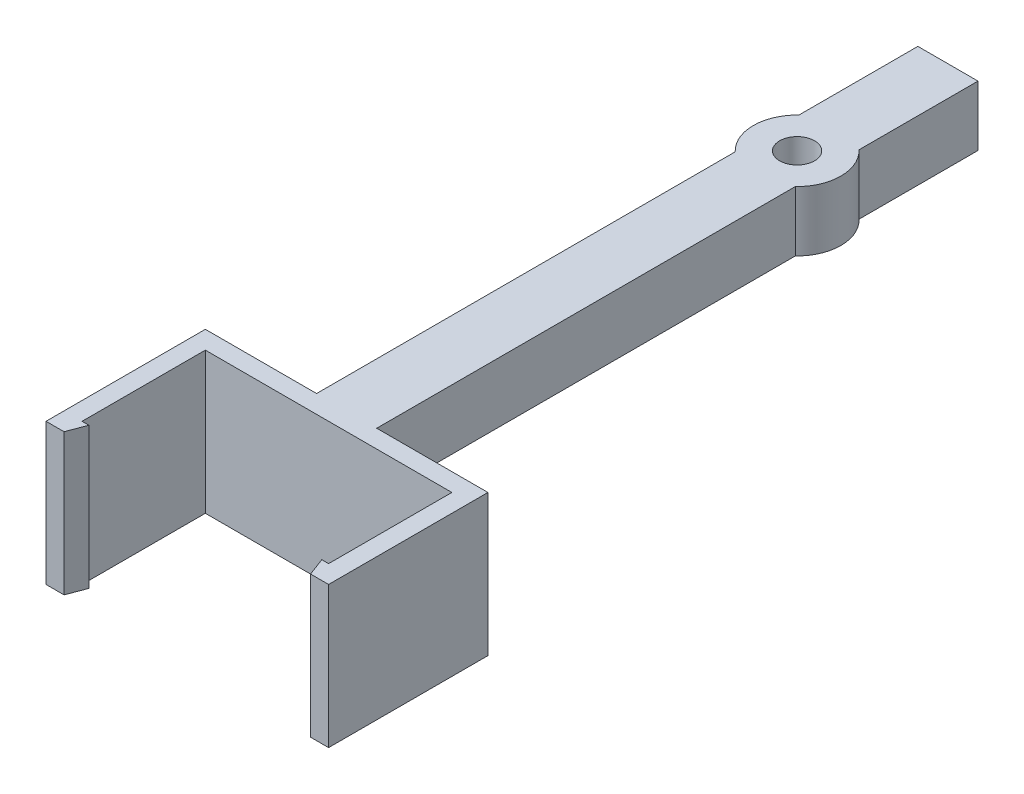
SolidWorks part; units mm, degrees
ref_plane "Front Plane" through (0, 0, 0) normal (0, 0, 1) x (1, 0, 0)
ref_plane "Top Plane" through (0, 0, 0) normal (0, 1, 0) x (1, 0, 0)
ref_plane "Right Plane" through (0, 0, 0) normal (1, 0, 0) x (0, 0, -1)
sketch "Sketch1" plane through (0, 0, 0) normal (0, 1, 0) x (1, 0, 0)
  line L0 (-23.5, 13.25) -> (-23.5, -13.25)
  line L1 (-20.5, 10.25) -> (20.5, 10.25)
  line L2 (-20.5, 10.25) -> (-20.5, -10.25)
  line L3 (-20.5, -10.25) -> (20.5, -10.25)
  line L4 (20.5, 10.25) -> (20.5, -10.25)
  line L5 (-20.5, 10.25) -> (20.5, -10.25) construction
  line L6 (-20.5, -10.25) -> (20.5, 10.25) construction
  line L7 (-23.5, -13.25) -> (23.5, -13.25)
  line L8 (23.5, 13.25) -> (23.5, -13.25)
  line L9 (-23.5, 13.25) -> (23.5, 13.25)
  point P0 (0, 0)
  dimension "D1" = 3
extrude "Boss-Extrude1" add sketch "Sketch1" along normal blind 31
sketch "Sketch3" plane through (0, 31, 0) normal (0, 1, 0) x (1, 0, 0)
  line L1 (-23.5, -13.25) -> (23.5, -13.25) construction
  line L2 (-20.5, -13.25) -> (20.5, -13.25)
  line L4 (20.5, -10.25) -> (-20.5, -10.25)
  line L5 (0, -10.25) -> (0, -13.25) construction
  line L6 (-20.5, -13.25) -> (-19.3661, -10.25)
  line L7 (20.5, -13.25) -> (19.3661, -10.25)
  line L8 (-19.3661, -10.25) -> (19.3661, -10.25)
  line M7 (-23.5, -13.25) -> (23.5, -13.25)
extrude "Cut-Extrude2" cut sketch "Sketch3" against normal blind 31 contours L5 L8 L6 M7 | L4 L5 L2 L7
sketch "Sketch4" plane through (0, 0, -13.25) normal (0, 0, -1) x (-1, 0, 0)
  line L0 (-23.5, 31) -> (23.5, 0) construction
  line L1 (23.5, 0) -> (23.5, 31) construction
  line L2 (23.5, 31) -> (-23.5, 0) construction
  line L3 (0, 15.5) -> (0, 19.4376) construction
  line L4 (-5, 20.5) -> (-5, 31) construction
  line L9 (-5, 10.5) -> (5, 20.5) construction
  line L10 (-5, 20.5) -> (5, 10.5) construction
  line L11 (-23.5, 31) -> (23.5, 31) construction
  line L12 (-5, 31) -> (5, 31) construction
  line L13 (5, 31) -> (5, 20.5) construction
  line L15 (-5, 31) -> (5, 31)
  line L16 (-5, 31) -> (-5, 21)
  line L17 (-5, 21) -> (5, 21)
  line L18 (5, 31) -> (5, 21)
extrude "Boss-Extrude3" add sketch "Sketch4" along normal blind 100
sketch "Sketch7" plane through (0, 21, 0) normal (0, -1, 0) x (1, 0, 0)
  line L0 (0, -113.25) -> (0, -63.0832) construction
  line L1 (5, -113.25) -> (-5, -113.25) construction
  circle A0 centre (0, -88.1666) radius 2.9
extrude "Cut-Extrude5" cut sketch "Sketch7" against normal blind 100
sketch "Sketch8" plane through (0, 21, 0) normal (0, -1, 0) x (-1, 0, 0)
  circle A0 centre (0, 88.1666) radius 7.2845
  circle A1 centre (0, 88.1666) radius 2.9
extrude "Boss-Extrude4" add sketch "Sketch8" against normal blind 10
sketch "Sketch10" plane through (-23.5, 0, 0) normal (-1, 0, 0) x (0, 0, 1)
  line L0 (13.25, 31) -> (13.25, 0) construction
  line L1 (-13.25, 0) -> (13.25, 0)
  line L2 (-13.25, 0) -> (-13.25, 7.4961)
  line L3 (-13.25, 7.4961) -> (13.25, 7.4961)
  line L4 (13.25, 0) -> (13.25, 7.4961)
extrude "Cut-Extrude6" cut sketch "Sketch10" against normal blind 105
